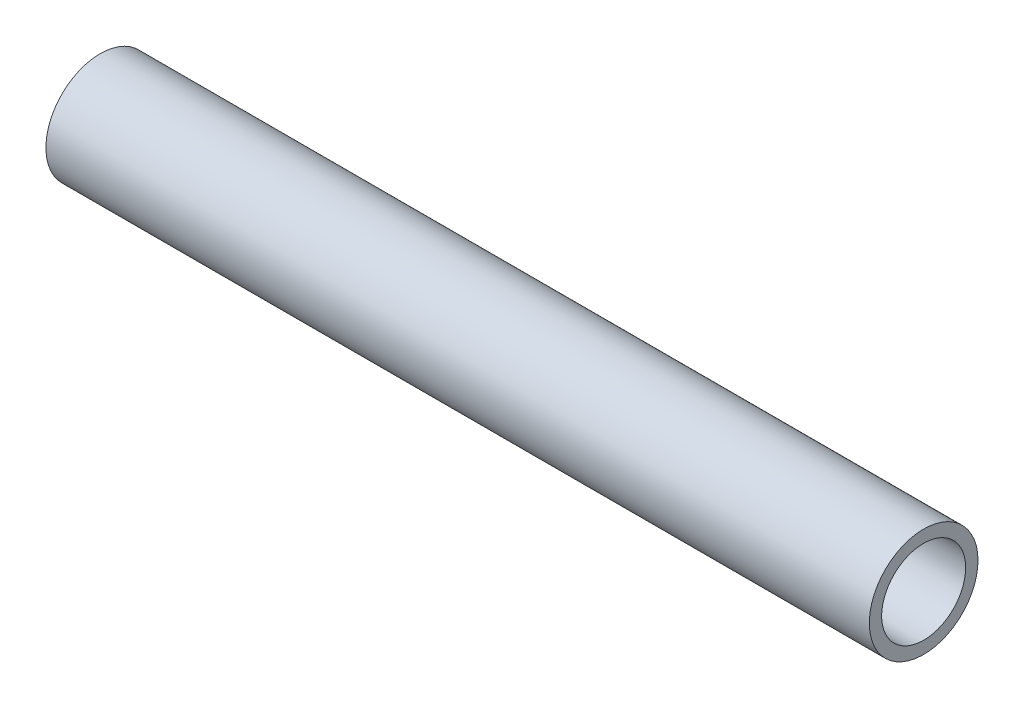
SolidWorks part; units mm, degrees
ref_plane "Front Plane" through (0, 0, 0) normal (0, 0, 1) x (1, 0, 0)
ref_plane "Top Plane" through (0, 0, 0) normal (0, 1, 0) x (1, 0, 0)
ref_plane "Right Plane" through (0, 0, 0) normal (1, 0, 0) x (0, 0, -1)
sketch "Sketch1" plane through (0, 0, 0) normal (1, 0, 0) x (0, 0, -1)
  circle A0 centre (0, 0) radius 5.1
  circle A1 centre (0, 0) radius 6.6
  dimension "D1" = 10.2
  dimension "D2" = 1.5
extrude "Boss-Extrude1" add sketch "Sketch1" along normal blind 100
